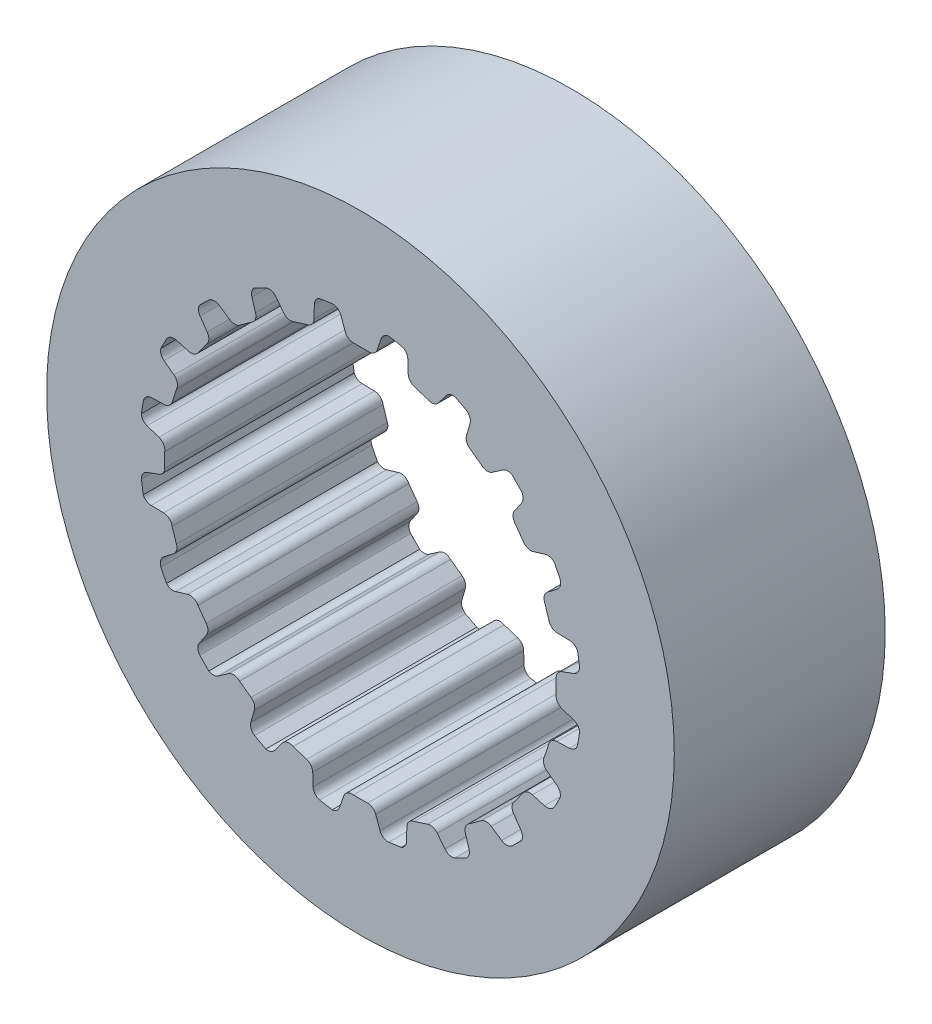
SolidWorks part; units mm, degrees
ref_plane "Front Plane" through (0, 0, 0) normal (0, 0, 1) x (1, 0, 0)
ref_plane "Top Plane" through (0, 0, 0) normal (0, 1, 0) x (1, 0, 0)
ref_plane "Right Plane" through (0, 0, 0) normal (1, 0, 0) x (0, 0, -1)
sketch "Sketch1" plane through (0, 0, 0) normal (0, 0, 1) x (1, 0, 0)
  line L0 (-0.1069, 2.9699) -> (0.1069, 2.9699)
  line L1 (0.3159, 3.2375) -> (0.2537, 3.0575)
  line L2 (-0.2964, 3.2367) -> (-0.2318, 3.0575)
  line L3 (-0.2964, 3.2367) -> (0.3159, 3.2375) construction
  line L4 (0, 3.3252) -> (0, 0) construction
  line L5 (-0.2318, 3.0575) -> (0.2537, 3.0575) construction
  line L6 (-0.4281, 3.3241) -> (0.4281, 3.3263) construction
  line L7 (0.7183, 3.1698) -> (0.7244, 2.9795)
  line L8 (0.816, 2.8576) -> (1.0195, 2.7915)
  line L9 (1.3009, 2.9815) -> (1.1862, 2.8295)
  line L10 (1.6627, 2.7927) -> (1.6097, 2.6099)
  line L11 (1.6591, 2.4655) -> (1.8322, 2.3398)
  line L12 (2.1585, 2.4335) -> (2.0025, 2.3245)
  line L13 (2.4443, 2.1423) -> (2.3374, 1.9847)
  line L14 (2.3398, 1.8322) -> (2.4655, 1.6591)
  line L15 (2.8049, 1.6474) -> (2.6228, 1.5919)
  line L16 (2.9866, 1.2821) -> (2.8363, 1.1653)
  line L17 (2.7915, 1.0195) -> (2.8576, 0.816)
  line L18 (3.1767, 0.7) -> (2.9863, 0.7035)
  line L19 (3.2367, 0.2964) -> (3.0575, 0.2318)
  line L20 (2.9699, 0.1069) -> (2.9699, -0.1069)
  line L21 (3.2375, -0.3159) -> (3.0575, -0.2537)
  line L22 (3.1698, -0.7183) -> (2.9795, -0.7244)
  line L23 (2.8576, -0.816) -> (2.7915, -1.0195)
  line L24 (2.9815, -1.3009) -> (2.8295, -1.1862)
  line L25 (2.7927, -1.6627) -> (2.6099, -1.6097)
  line L26 (2.4655, -1.6591) -> (2.3398, -1.8322)
  line L27 (2.4335, -2.1585) -> (2.3245, -2.0025)
  line L28 (2.1423, -2.4443) -> (1.9847, -2.3374)
  line L29 (1.8322, -2.3398) -> (1.6591, -2.4655)
  line L30 (1.6474, -2.8049) -> (1.5919, -2.6228)
  line L31 (1.2821, -2.9866) -> (1.1653, -2.8363)
  line L32 (1.0195, -2.7915) -> (0.816, -2.8576)
  line L33 (0.7, -3.1767) -> (0.7035, -2.9863)
  line L34 (0.2964, -3.2367) -> (0.2318, -3.0575)
  line L35 (0.1069, -2.9699) -> (-0.1069, -2.9699)
  line L36 (-0.3159, -3.2375) -> (-0.2537, -3.0575)
  line L37 (-0.7183, -3.1698) -> (-0.7244, -2.9795)
  line L38 (-0.816, -2.8576) -> (-1.0195, -2.7915)
  line L39 (-1.3009, -2.9815) -> (-1.1862, -2.8295)
  line L40 (-1.6627, -2.7927) -> (-1.6097, -2.6099)
  line L41 (-1.6591, -2.4655) -> (-1.8322, -2.3398)
  line L42 (-2.1585, -2.4335) -> (-2.0025, -2.3245)
  line L43 (-2.4443, -2.1423) -> (-2.3374, -1.9847)
  line L44 (-2.3398, -1.8322) -> (-2.4655, -1.6591)
  line L45 (-2.8049, -1.6474) -> (-2.6228, -1.5919)
  line L46 (-2.9866, -1.2821) -> (-2.8363, -1.1653)
  line L47 (-2.7915, -1.0195) -> (-2.8576, -0.816)
  line L48 (-3.1767, -0.7) -> (-2.9863, -0.7035)
  line L49 (-3.2367, -0.2964) -> (-3.0575, -0.2318)
  line L50 (-2.9699, -0.1069) -> (-2.9699, 0.1069)
  line L51 (-3.2375, 0.3159) -> (-3.0575, 0.2537)
  line L52 (-3.1698, 0.7183) -> (-2.9795, 0.7244)
  line L53 (-2.8576, 0.816) -> (-2.7915, 1.0195)
  line L54 (-2.9815, 1.3009) -> (-2.8295, 1.1862)
  line L55 (-2.7927, 1.6627) -> (-2.6099, 1.6097)
  line L56 (-2.4655, 1.6591) -> (-2.3398, 1.8322)
  line L57 (-2.4335, 2.1585) -> (-2.3245, 2.0025)
  line L58 (-2.1423, 2.4443) -> (-1.9847, 2.3374)
  line L59 (-1.8322, 2.3398) -> (-1.6591, 2.4655)
  line L60 (-1.6474, 2.8049) -> (-1.5919, 2.6228)
  line L61 (-1.2821, 2.9866) -> (-1.1653, 2.8363)
  line L62 (-1.0195, 2.7915) -> (-0.816, 2.8576)
  line L63 (-0.7, 3.1767) -> (-0.7035, 2.9863)
  line L64 (0.4281, 3.3263) -> (0.62, 3.2938)
  line L65 (1.4351, 3.0312) -> (1.6075, 2.9409)
  line L66 (2.3015, 2.4394) -> (2.4376, 2.3003)
  line L67 (2.9427, 1.6088) -> (3.0291, 1.4344)
  line L68 (3.2958, 0.6207) -> (3.3241, 0.4281)
  line L69 (3.3263, -0.4281) -> (3.2938, -0.62)
  line L70 (3.0312, -1.4351) -> (2.9409, -1.6075)
  line L71 (2.4394, -2.3015) -> (2.3003, -2.4376)
  line L72 (1.6088, -2.9427) -> (1.4344, -3.0291)
  line L73 (0.6207, -3.2958) -> (0.4281, -3.3241)
  line L74 (-0.4281, -3.3263) -> (-0.62, -3.2938)
  line L75 (-1.4351, -3.0312) -> (-1.6075, -2.9409)
  line L76 (-2.3015, -2.4394) -> (-2.4376, -2.3003)
  line L77 (-2.9427, -1.6088) -> (-3.0291, -1.4344)
  line L78 (-3.2958, -0.6207) -> (-3.3241, -0.4281)
  line L79 (-3.3263, 0.4281) -> (-3.2938, 0.62)
  line L80 (-3.0312, 1.4351) -> (-2.9409, 1.6075)
  line L81 (-2.4394, 2.3015) -> (-2.3003, 2.4376)
  line L82 (-1.6088, 2.9427) -> (-1.4344, 3.0291)
  line L83 (-0.6207, 3.2958) -> (-0.4281, 3.3241)
  arc A0 (0.2537, 3.0575) -> (0.1069, 2.9699) centre (0.1283, 3.1009) cw
  arc A1 (-0.2318, 3.0575) -> (-0.1069, 2.9699) centre (-0.1069, 3.1026) ccw
  arc A2 (0.62, 3.2938) -> (0.7183, 3.1698) centre (0.5856, 3.1656) cw
  arc A3 (0.7244, 2.9795) -> (0.816, 2.8576) centre (0.857, 2.9838) ccw
  arc A4 (-0.4281, 3.3241) -> (-0.2964, 3.2367) centre (-0.4213, 3.1916) cw
  arc A5 (0.4281, 3.3263) -> (0.3159, 3.2375) centre (0.4413, 3.1942) ccw
  arc A6 (1.1862, 2.8295) -> (1.0195, 2.7915) centre (1.0802, 2.9095) cw
  arc A7 (1.4351, 3.0312) -> (1.3009, 2.9815) centre (1.4068, 2.9015) ccw
  arc A8 (1.6075, 2.9409) -> (1.6627, 2.7927) centre (1.5352, 2.8297) cw
  arc A9 (1.6097, 2.6099) -> (1.6591, 2.4655) centre (1.7371, 2.5729) ccw
  arc A10 (2.0025, 2.3245) -> (1.8322, 2.3398) centre (1.9264, 2.4332) cw
  arc A11 (2.3015, 2.4394) -> (2.1585, 2.4335) centre (2.2346, 2.3248) ccw
  arc A12 (2.4376, 2.3003) -> (2.4443, 2.1423) centre (2.3345, 2.2168) cw
  arc A13 (2.3374, 1.9847) -> (2.3398, 1.8322) centre (2.4472, 1.9102) ccw
  arc A14 (2.6228, 1.5919) -> (2.4655, 1.6591) centre (2.5841, 1.7189) cw
  arc A15 (2.9427, 1.6088) -> (2.8049, 1.6474) centre (2.8436, 1.5205) ccw
  arc A16 (3.0291, 1.4344) -> (2.9866, 1.2821) centre (2.9052, 1.3869) cw
  arc A17 (2.8363, 1.1653) -> (2.7915, 1.0195) centre (2.9177, 1.0605) ccw
  arc A18 (2.9863, 0.7035) -> (2.8576, 0.816) centre (2.9887, 0.8362) cw
  arc A19 (3.2958, 0.6207) -> (3.1767, 0.7) centre (3.1743, 0.5673) ccw
  arc A20 (3.3241, 0.4281) -> (3.2367, 0.2964) centre (3.1916, 0.4213) cw
  arc A21 (3.0575, 0.2318) -> (2.9699, 0.1069) centre (3.1026, 0.1069) ccw
  arc A22 (3.0575, -0.2537) -> (2.9699, -0.1069) centre (3.1009, -0.1283) cw
  arc A23 (3.3263, -0.4281) -> (3.2375, -0.3159) centre (3.1942, -0.4413) ccw
  arc A24 (3.2938, -0.62) -> (3.1698, -0.7183) centre (3.1656, -0.5856) cw
  arc A25 (2.9795, -0.7244) -> (2.8576, -0.816) centre (2.9838, -0.857) ccw
  arc A26 (2.8295, -1.1862) -> (2.7915, -1.0195) centre (2.9095, -1.0802) cw
  arc A27 (3.0312, -1.4351) -> (2.9815, -1.3009) centre (2.9015, -1.4068) ccw
  arc A28 (2.9409, -1.6075) -> (2.7927, -1.6627) centre (2.8297, -1.5352) cw
  arc A29 (2.6099, -1.6097) -> (2.4655, -1.6591) centre (2.5729, -1.7371) ccw
  arc A30 (2.3245, -2.0025) -> (2.3398, -1.8322) centre (2.4332, -1.9264) cw
  arc A31 (2.4394, -2.3015) -> (2.4335, -2.1585) centre (2.3248, -2.2346) ccw
  arc A32 (2.3003, -2.4376) -> (2.1423, -2.4443) centre (2.2168, -2.3345) cw
  arc A33 (1.9847, -2.3374) -> (1.8322, -2.3398) centre (1.9102, -2.4472) ccw
  arc A34 (1.5919, -2.6228) -> (1.6591, -2.4655) centre (1.7189, -2.5841) cw
  arc A35 (1.6088, -2.9427) -> (1.6474, -2.8049) centre (1.5205, -2.8436) ccw
  arc A36 (1.4344, -3.0291) -> (1.2821, -2.9866) centre (1.3869, -2.9052) cw
  arc A37 (1.1653, -2.8363) -> (1.0195, -2.7915) centre (1.0605, -2.9177) ccw
  arc A38 (0.7035, -2.9863) -> (0.816, -2.8576) centre (0.8362, -2.9887) cw
  arc A39 (0.6207, -3.2958) -> (0.7, -3.1767) centre (0.5673, -3.1743) ccw
  arc A40 (0.4281, -3.3241) -> (0.2964, -3.2367) centre (0.4213, -3.1916) cw
  arc A41 (0.2318, -3.0575) -> (0.1069, -2.9699) centre (0.1069, -3.1026) ccw
  arc A42 (-0.2537, -3.0575) -> (-0.1069, -2.9699) centre (-0.1283, -3.1009) cw
  arc A43 (-0.4281, -3.3263) -> (-0.3159, -3.2375) centre (-0.4413, -3.1942) ccw
  arc A44 (-0.62, -3.2938) -> (-0.7183, -3.1698) centre (-0.5856, -3.1656) cw
  arc A45 (-0.7244, -2.9795) -> (-0.816, -2.8576) centre (-0.857, -2.9838) ccw
  arc A46 (-1.1862, -2.8295) -> (-1.0195, -2.7915) centre (-1.0802, -2.9095) cw
  arc A47 (-1.4351, -3.0312) -> (-1.3009, -2.9815) centre (-1.4068, -2.9015) ccw
  arc A48 (-1.6075, -2.9409) -> (-1.6627, -2.7927) centre (-1.5352, -2.8297) cw
  arc A49 (-1.6097, -2.6099) -> (-1.6591, -2.4655) centre (-1.7371, -2.5729) ccw
  arc A50 (-2.0025, -2.3245) -> (-1.8322, -2.3398) centre (-1.9264, -2.4332) cw
  arc A51 (-2.3015, -2.4394) -> (-2.1585, -2.4335) centre (-2.2346, -2.3248) ccw
  arc A52 (-2.4376, -2.3003) -> (-2.4443, -2.1423) centre (-2.3345, -2.2168) cw
  arc A53 (-2.3374, -1.9847) -> (-2.3398, -1.8322) centre (-2.4472, -1.9102) ccw
  arc A54 (-2.6228, -1.5919) -> (-2.4655, -1.6591) centre (-2.5841, -1.7189) cw
  arc A55 (-2.9427, -1.6088) -> (-2.8049, -1.6474) centre (-2.8436, -1.5205) ccw
  arc A56 (-3.0291, -1.4344) -> (-2.9866, -1.2821) centre (-2.9052, -1.3869) cw
  arc A57 (-2.8363, -1.1653) -> (-2.7915, -1.0195) centre (-2.9177, -1.0605) ccw
  arc A58 (-2.9863, -0.7035) -> (-2.8576, -0.816) centre (-2.9887, -0.8362) cw
  arc A59 (-3.2958, -0.6207) -> (-3.1767, -0.7) centre (-3.1743, -0.5673) ccw
  arc A60 (-3.3241, -0.4281) -> (-3.2367, -0.2964) centre (-3.1916, -0.4213) cw
  arc A61 (-3.0575, -0.2318) -> (-2.9699, -0.1069) centre (-3.1026, -0.1069) ccw
  arc A62 (-3.0575, 0.2537) -> (-2.9699, 0.1069) centre (-3.1009, 0.1283) cw
  arc A63 (-3.3263, 0.4281) -> (-3.2375, 0.3159) centre (-3.1942, 0.4413) ccw
  arc A64 (-3.2938, 0.62) -> (-3.1698, 0.7183) centre (-3.1656, 0.5856) cw
  arc A65 (-2.9795, 0.7244) -> (-2.8576, 0.816) centre (-2.9838, 0.857) ccw
  arc A66 (-2.8295, 1.1862) -> (-2.7915, 1.0195) centre (-2.9095, 1.0802) cw
  arc A67 (-3.0312, 1.4351) -> (-2.9815, 1.3009) centre (-2.9015, 1.4068) ccw
  arc A68 (-2.9409, 1.6075) -> (-2.7927, 1.6627) centre (-2.8297, 1.5352) cw
  arc A69 (-2.6099, 1.6097) -> (-2.4655, 1.6591) centre (-2.5729, 1.7371) ccw
  arc A70 (-2.3245, 2.0025) -> (-2.3398, 1.8322) centre (-2.4332, 1.9264) cw
  arc A71 (-2.4394, 2.3015) -> (-2.4335, 2.1585) centre (-2.3248, 2.2346) ccw
  arc A72 (-2.3003, 2.4376) -> (-2.1423, 2.4443) centre (-2.2168, 2.3345) cw
  arc A73 (-1.9847, 2.3374) -> (-1.8322, 2.3398) centre (-1.9102, 2.4472) ccw
  arc A74 (-1.5919, 2.6228) -> (-1.6591, 2.4655) centre (-1.7189, 2.5841) cw
  arc A75 (-1.6088, 2.9427) -> (-1.6474, 2.8049) centre (-1.5205, 2.8436) ccw
  arc A76 (-1.4344, 3.0291) -> (-1.2821, 2.9866) centre (-1.3869, 2.9052) cw
  arc A77 (-1.1653, 2.8363) -> (-1.0195, 2.7915) centre (-1.0605, 2.9177) ccw
  arc A78 (-0.7035, 2.9863) -> (-0.816, 2.8576) centre (-0.8362, 2.9887) cw
  arc A79 (-0.6207, 3.2958) -> (-0.7, 3.1767) centre (-0.5673, 3.1743) ccw
  circle A80 centre (0, 0) radius 4.7625
  point P14 (0, 2.9699)
  point P247 (0, 0)
  dimension "D4" = 0.1327
  dimension "D8" = 20
  dimension "D9" = 9.525
  dimension "D1" = 2.9699
  dimension "D2" = 0.2139
  dimension "D3" = 0.1904
  dimension "D5" = 0.0877
  dimension "D6" = 0.4855
  dimension "D7" = 0.8563
extrude "Boss-Extrude1" add sketch "Sketch1" along normal mid plane 3.2004
